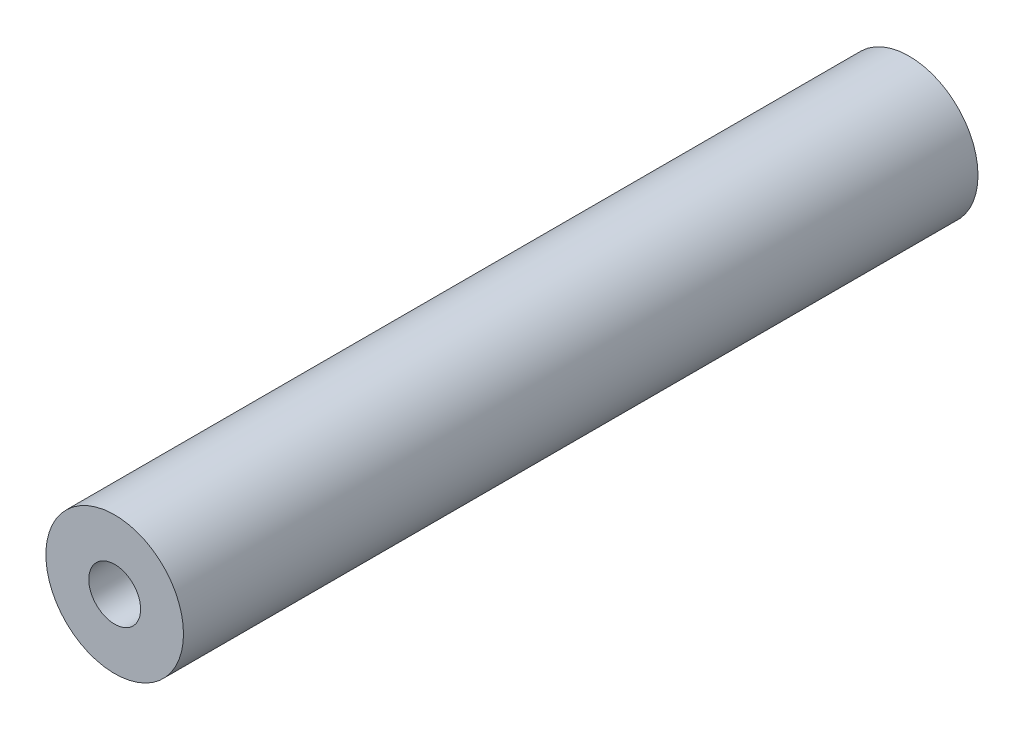
SolidWorks part; units mm, degrees
material "1060 Alloy"
ref_plane "Front Plane" through (0, 0, 0) normal (0, 0, 1) x (1, 0, 0)
ref_plane "Top Plane" through (0, 0, 0) normal (0, 1, 0) x (1, 0, 0)
ref_plane "Right Plane" through (0, 0, 0) normal (1, 0, 0) x (0, 0, -1)
sketch "Sketch1" plane through (0, 0, 0) normal (0, 0, 1) x (1, 0, 0)
  circle A0 centre (0, 0) radius 3
  dimension "D1" = 6
extrude "Boss-Extrude1" add sketch "Sketch1" along normal blind 34.64
hole_wizard "#4-40 Tapped Hole1" positions "Sketch2" profile "Sketch3" tap size "#4-40" standard "ANSI Inch" end condition through all
sketch "Sketch2" plane through (0, 0, 34.64) normal (0, 0, 1) x (1, 0, 0)
  point P0 (0, 0)
sketch "Sketch3" plane through (0, 0, 34.64) normal (1, 0, 0) x (0, -1, 0)
  line L0 (0, 0) -> (0, 34.64)
  line L1 (0, 34.64) -> (1.1303, 34.64)
  line L2 (1.1303, 34.64) -> (1.1303, 0)
  line L5 (1.1303, 0) -> (0, 0)
  line L11 (0, -6.35) -> (0, 107.95) construction
  dimension "Thru Tap Drill Dia." = 2.2606
  dimension "Thru Tap Drill Depth" = 34.64
cosmetic thread "Hole Thread1"
